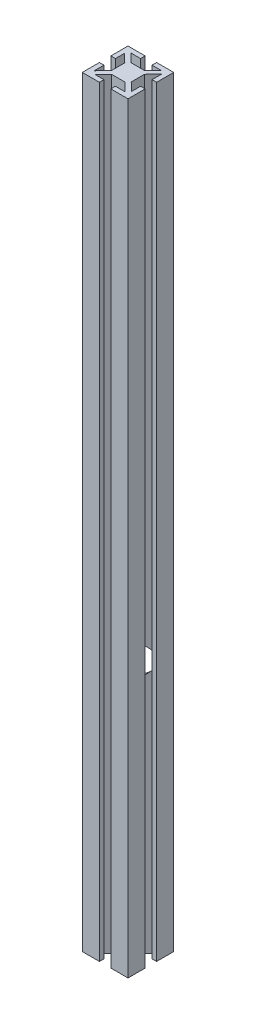
SolidWorks part; units mm, degrees
material "1060 Alloy"
ref_plane "Front Plane" through (0, 0, 0) normal (0, 0, 1) x (1, 0, 0)
ref_plane "Top Plane" through (0, 0, 0) normal (0, 1, 0) x (1, 0, 0)
ref_plane "Right Plane" through (0, 0, 0) normal (1, 0, 0) x (0, 0, -1)
sketch "Sketch1" plane through (0, 0, 0) normal (0, 1, 0) x (1, 0, 0)
  line L1 (-10, 10) -> (10, 10) construction
  line L2 (-10, 10) -> (-10, -10) construction
  line L3 (-10, -10) -> (10, -10) construction
  line L4 (10, 10) -> (10, -10) construction
  line L5 (-10, 10) -> (10, -10) construction
  line L6 (-10, -10) -> (10, 10) construction
  circle A0 centre (0, 0) radius 2
  point P0 (0, 0)
  dimension "D3" = 4
  dimension "D1" = 20
  dimension "D2" = 20
sketch "Sketch2" plane through (0, 0, 0) normal (0, 1, 0) x (1, 0, 0)
  line L0 (-10, 2.5) -> (-10, -2.5) construction
  line L1 (-10, 10) -> (-10, -10) construction
  line L2 (-10, -10) -> (-10, -2.5)
  line L3 (-10, -2.5) -> (-8, -2.5)
  line L4 (-8, -2.5) -> (-8, -6.7683)
  line L5 (-8, -6.7683) -> (-4.3583, -2.9445)
  line L6 (-4.3583, -2.9445) -> (-2.91, -4.3238)
  line L7 (-2.91, -4.3238) -> (-6.4243, -8)
  line L8 (-6.4243, -8) -> (-2.5, -8)
  line L9 (-2.5, -8) -> (-2.5, -10)
  line L10 (-10, -10) -> (10, -10) construction
  line L11 (-2.5, -10) -> (-10, -10)
  line L12 (-2.5, -10) -> (2.5, -10) construction
  line L14 (-10, -10) -> (10, 10) construction
  line L15 (-10, 2.5) -> (-10, 10)
  line L16 (-10, 10) -> (-2.5, 10)
  line L17 (-2.5, 10) -> (-2.5, 8)
  line L18 (-2.5, 8) -> (-6.7683, 8)
  line L19 (-6.7683, 8) -> (-2.9445, 4.3583)
  line L20 (-2.9445, 4.3583) -> (-4.3238, 2.91)
  line L21 (-4.3238, 2.91) -> (-8, 6.4243)
  line L22 (-8, 6.4243) -> (-8, 2.5)
  line L23 (-8, 2.5) -> (-10, 2.5)
  line L24 (2.5, 10) -> (10, 10)
  line L25 (10, 10) -> (10, 2.5)
  line L26 (10, 2.5) -> (8, 2.5)
  line L27 (8, 2.5) -> (8, 6.7683)
  line L28 (8, 6.7683) -> (4.3583, 2.9445)
  line L29 (4.3583, 2.9445) -> (2.91, 4.3238)
  line L30 (2.91, 4.3238) -> (6.4243, 8)
  line L31 (6.4243, 8) -> (2.5, 8)
  line L32 (2.5, 8) -> (2.5, 10)
  line L33 (10, -2.5) -> (10, -10)
  line L34 (10, -10) -> (2.5, -10)
  line L35 (2.5, -10) -> (2.5, -8)
  line L36 (2.5, -8) -> (6.7683, -8)
  line L37 (6.7683, -8) -> (2.9445, -4.3583)
  line L38 (2.9445, -4.3583) -> (4.3238, -2.91)
  line L39 (4.3238, -2.91) -> (8, -6.4243)
  line L40 (8, -6.4243) -> (8, -2.5)
  line L41 (8, -2.5) -> (10, -2.5)
  line L42 (-10, 10) -> (10, -10) construction
  line L43 (-4.3238, 4.3238) -> (4.3238, 4.3238)
  line L44 (-4.3238, 4.3238) -> (-4.3238, -4.3238)
  line L45 (-4.3238, -4.3238) -> (4.3238, -4.3238)
  line L46 (4.3238, 4.3238) -> (4.3238, -4.3238)
  line L47 (-4.3238, 4.3238) -> (4.3238, -4.3238) construction
  line L48 (-4.3238, -4.3238) -> (4.3238, 4.3238) construction
  point P5 (-10, 0)
  point P11 (0, 0)
  point P14 (-3.6341, -3.6341)
  point P19 (0, -10)
  dimension "D1" = 5
  dimension "D2" = 5
  dimension "D3" = 2
  dimension "D4" = 2
  dimension "D5" = 2
  dimension "D6" = 2
  dimension "D7" = 9
  dimension "D8" = 4
extrude "Boss-Extrude1" add sketch "Sketch2" along normal blind 333 contours L45 L44 L6 L5 L4 L3 L2 L11 L9 L8 L7 | L46 L29 L43 L20 L44 L6 L45 L38 | L39 L46 L45 L38 L37 L36 L35 L34 L33 L41 L40 | L43 L46 L29 L28 L27 L26 L25 L24 L32 L31 L30 | L44 L43 L20 L19 L18 L17 L16 L15 L23 L22 L21 | L46 L38 L45 | L46 L43 L29
sketch "Sketch4" plane through (10, 0, 0) normal (1, 0, 0) x (0, 0, -1)
  line L0 (0.0337, 333) -> (0.0337, 281.6) construction
  line L1 (2.9773, 333) -> (-2.91, 333) construction
  line L2 (0.0337, 281.6) -> (0.0337, 268.6) construction
  line L3 (0.0337, 268.6) -> (0.0337, 248.6) construction
  circle A0 centre (0.0337, 281.6) radius 2
  circle A1 centre (0.0337, 268.6) radius 2
  circle A2 centre (0.0337, 248.6) radius 2
  dimension "D2" = 4
  dimension "D5" = 4
  dimension "D6" = 4
  dimension "D1" = 51.4
  dimension "D3" = 13
  dimension "D4" = 20
extrude "Cut-Extrude1" [suppressed] cut sketch "Sketch4" against normal blind 110 contours A1 | A2 | A0
sketch "Sketch5" plane through (0, 0, -10) normal (0, 0, -1) x (-1, 0, 0)
  line L0 (0.0337, 333) -> (0.0337, 293.49) construction
  line L1 (2.9773, 333) -> (-2.91, 333) construction
  circle A0 centre (0.0337, 293.49) radius 4.5
  dimension "D2" = 9
  dimension "D1" = 39.51
extrude "Cut-Extrude2" [suppressed] cut sketch "Sketch5" against normal blind 110 contours A0
sketch "Sketch7" [suppressed] plane through (0, 0, -10) normal (0, 0, -1) x (-1, 0, 0)
  line L0 (0, 0) -> (0, 28) construction
  line L1 (6.5, 21.8611) -> (-6.5, 21.8611) construction
  line L2 (6.5, 6.8611) -> (-6.5, 6.8611) construction
  line L3 (-6.5, 6.8611) -> (-6.5, 21.8611) construction
  line L4 (6.5, 21.8611) -> (6.5, 6.8611) construction
  line L5 (10, 320) -> (10, 0) construction
  circle A0 centre (6.5, 21.8611) radius 2.1
  circle A1 centre (6.5, 6.8611) radius 2.1
  circle A2 centre (-6.5, 21.8611) radius 2.1
  circle A3 centre (-6.5, 6.8611) radius 2.1
  point P6 (0, 21.8611)
  point P9 (0, 6.8611)
  dimension "D3" = 4.2
  dimension "D4" = 4.2
  dimension "D1" = 28
  dimension "D2" = 3.5
  dimension "D5" = 15
sketch "Sketch9" plane through (-10, 0, 0) normal (-1, 0, 0) x (0, 0, 1)
  line L0 (0, 0) -> (0, 28) construction
  line L1 (6.5, 6) -> (-6.5, 6) construction
  line L2 (-6.5, 6) -> (-6.5, 21) construction
  line L3 (-6.5, 21) -> (6.5, 21) construction
  line L4 (6.5, 21) -> (6.5, 6) construction
  line L5 (10, 333) -> (10, 0) construction
  line L6 (-10, 0) -> (10, 0) construction
  circle A0 centre (6.5, 6) radius 2.1
  circle A1 centre (6.5, 21) radius 2.1
  circle A2 centre (-6.5, 21) radius 2.1
  circle A3 centre (-6.5, 6) radius 2.1
  point P6 (0, 6)
  dimension "D2" = 4.2
  dimension "D1" = 28
  dimension "D3" = 15
  dimension "D4" = 3.5
  dimension "D5" = 6
extrude "Cut-Extrude4" [suppressed] cut sketch "Sketch9" against normal through all
sketch "Sketch10" plane through (0, 0, -10) normal (0, 0, -1) x (-1, 0, 0)
  line L0 (0, 0) -> (0, 111) construction
  circle A0 centre (0, 111) radius 7
  dimension "D2" = 14
  dimension "D1" = 111
extrude "Cut-Extrude5" cut sketch "Sketch10" against normal blind 10
sketch "Sketch11" plane through (0, 0, 10) normal (0, 0, 1) x (1, 0, 0)
  line L0 (0.0337, 333) -> (0.0337, 325) construction
  line L1 (-2.91, 333) -> (2.9773, 333) construction
  circle A0 centre (0.0337, 325) radius 2
  dimension "D2" = 4
  dimension "D1" = 8
extrude "Cut-Extrude6" cut sketch "Sketch11" against normal blind 50
sketch "Sketch12" plane through (0, 0, 10) normal (0, 0, 1) x (1, 0, 0)
  circle A0 centre (0, 111) radius 2
  circle A1 centre (0, 111) radius 7
  circle A2 centre (0, 111) radius 7 construction
  dimension "D2" = 4
  dimension "D1" = 0
extrude "Cut-Extrude7" cut sketch "Sketch12" against normal blind 50 contours A0
sketch "Sketch13" plane through (0, 0, 10) normal (0, 0, 1) x (1, 0, 0)
  line L0 (0, 0) -> (0, 10) construction
  circle A0 centre (0, 10) radius 2
  dimension "D2" = 4
  dimension "D1" = 10
extrude "Cut-Extrude8" cut sketch "Sketch13" against normal blind 50 contours A0
